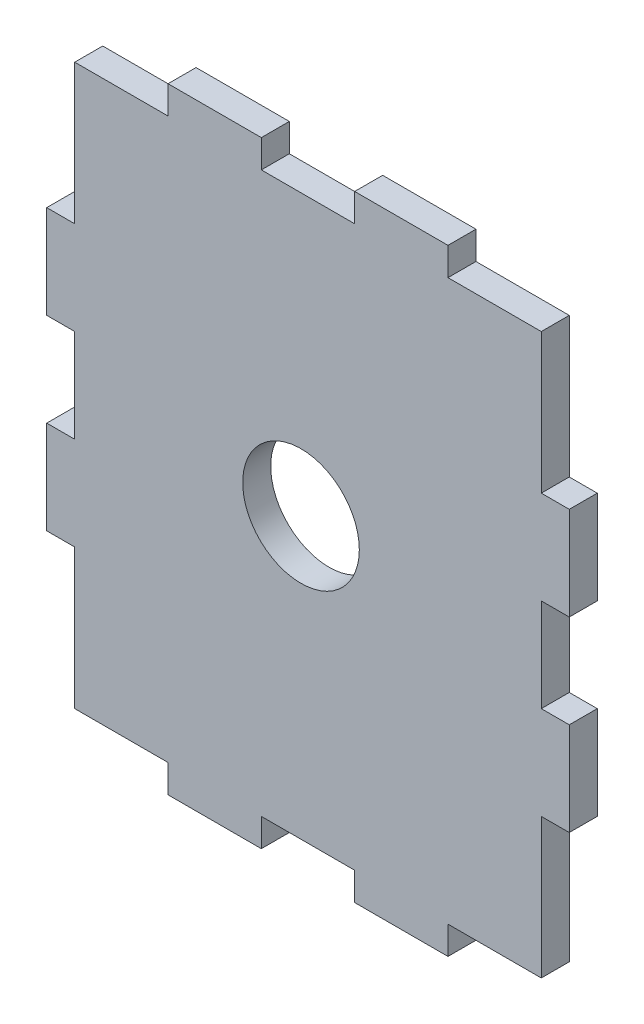
SolidWorks part; units mm, degrees
ref_plane "Plano frontal" through (0, 0, 0) normal (0, 0, 1) x (1, 0, 0)
ref_plane "Plano superior" through (0, 0, 0) normal (0, 1, 0) x (1, 0, 0)
ref_plane "Plano direito" through (0, 0, 0) normal (1, 0, 0) x (0, 0, -1)
sketch "Esboço2" plane through (0, 0, 0) normal (0, 0, 1) x (1, 0, 0)
  line L0 (-40, 0) -> (-20, 0)
  line L1 (-20, 0) -> (-20, 6)
  line L2 (-20, 6) -> (0, 6)
  line L3 (0, 6) -> (0, 0)
  line L4 (0, 0) -> (20, 0)
  line L5 (20, 0) -> (20, 6)
  line L6 (20, 6) -> (40, 6)
  line L7 (40, 6) -> (40, 0)
  line L8 (40, 0) -> (60, 0)
  line L9 (60, 0) -> (60, -30)
  line L10 (60, -30) -> (66, -30)
  line L11 (66, -30) -> (66, -50)
  line L12 (66, -50) -> (60, -50)
  line L13 (60, -50) -> (60, -70)
  line L14 (60, -70) -> (66, -70)
  line L15 (66, -70) -> (66, -90)
  line L16 (66, -90) -> (60, -90)
  line L17 (60, -90) -> (60, -120)
  line L18 (60, -120) -> (40, -120)
  line L19 (40, -120) -> (40, -126)
  line L20 (40, -126) -> (20, -126)
  line L21 (20, -126) -> (20, -120)
  line L22 (20, -120) -> (0, -120)
  line L23 (0, -120) -> (0, -126)
  line L24 (0, -126) -> (-20, -126)
  line L25 (-20, -126) -> (-20, -120)
  line L26 (-20, -120) -> (-40, -120)
  line L27 (-40, -120) -> (-40, -90)
  line L28 (-40, -90) -> (-46, -90)
  line L29 (-46, -90) -> (-46, -70)
  line L30 (-46, -70) -> (-40, -70)
  line L31 (-40, -70) -> (-40, -50)
  line L32 (-40, -50) -> (-46, -50)
  line L33 (-46, -50) -> (-46, -30)
  line L34 (-46, -30) -> (-40, -30)
  line L35 (-40, -30) -> (-40, 0)
  line L36 (10, 0) -> (10, -120) construction
  line L37 (-40, -60) -> (60, -60) construction
  circle A0 centre (8.5, -60) radius 12.5
  dimension "D15" = 25
  dimension "D1" = 6
  dimension "D2" = 6
  dimension "D3" = 100
  dimension "D4" = 20
  dimension "D5" = 20
  dimension "D6" = 30
  dimension "D7" = 20
  dimension "D8" = 30
  dimension "D9" = 6
  dimension "D10" = 6
  dimension "D11" = 6
  dimension "D12" = 6
  dimension "D13" = 120
  dimension "D14" = 20
  dimension "D16" = 48.5
extrude "Ressalto-extrusão8" add sketch "Esboço2" along normal blind 6
